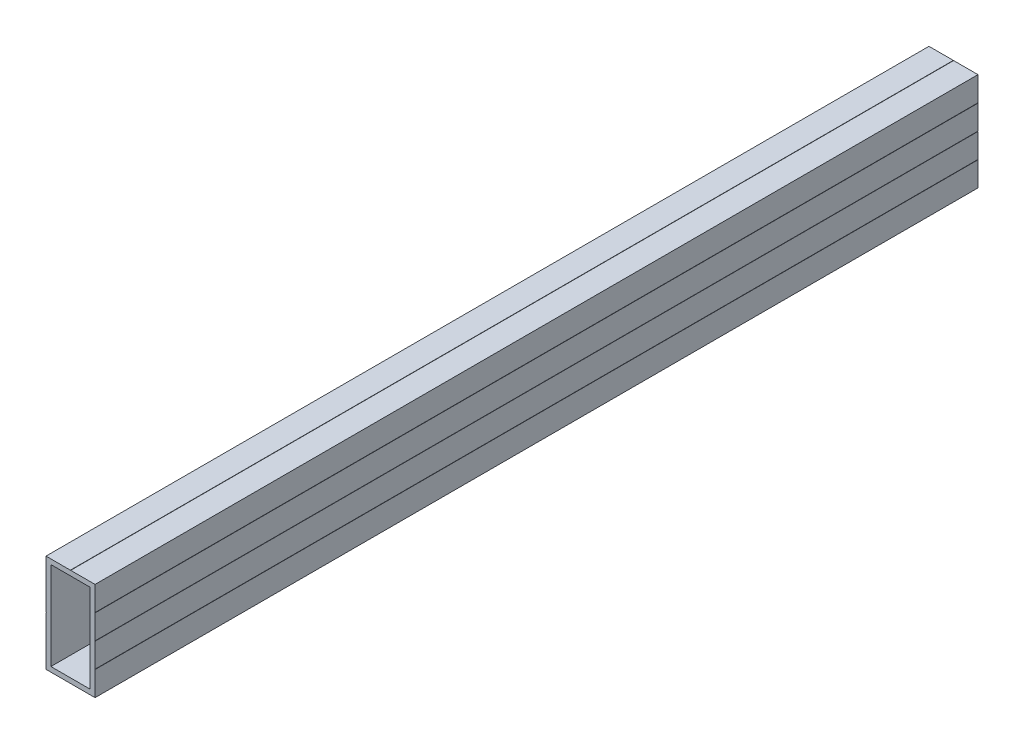
SolidWorks part; units mm, degrees
ref_plane "Front Plane" through (0, 0, 0) normal (0, 0, 1) x (1, 0, 0)
ref_plane "Top Plane" through (0, 0, 0) normal (0, 1, 0) x (1, 0, 0)
ref_plane "Right Plane" through (0, 0, 0) normal (1, 0, 0) x (0, 0, -1)
ref_plane "Plane1" through (12.7, 0, 0) normal (1, 0, 0) x (0, 0, -1)
sketch "Sketch1" plane through (12.7, 0, 0) normal (1, 0, 0) x (0, 0, -1)
  line L0 (-749.3, 25.4) -> (-749.3, -25.4)
  line L1 (-749.3, -25.4) -> (749.3, -25.4)
  line L2 (749.3, -25.4) -> (749.3, 25.4)
  line L3 (749.3, 25.4) -> (-749.3, 25.4)
extrude "Boss-Extrude1" add sketch "Sketch1" against normal blind 25.4
sketch "Sketch2" plane through (0, 0, 749.3) normal (0, 0, 1) x (1, 0, 0)
  line L0 (0.0762, 25.4) -> (-0.0762, 25.4)
  line L1 (-0.0762, 25.4) -> (0.0762, 25.2476)
  line L2 (0.0762, 25.2476) -> (0.0762, 25.4)
extrude "Cut-Extrude1" cut sketch "Sketch2" against normal blind 1498.6
sketch "Sketch3" plane through (0, 0, 749.3) normal (0, 0, 1) x (1, 0, 0)
  line L0 (12.7, 12.6238) -> (12.7, 12.7762)
  line L1 (12.7, 12.7762) -> (12.5476, 12.7762)
  line L2 (12.5476, 12.7762) -> (12.7, 12.6238)
extrude "Cut-Extrude2" cut sketch "Sketch3" against normal through all
sketch "Sketch4" plane through (0, 0, 749.3) normal (0, 0, 1) x (1, 0, 0)
  line L0 (12.7, -0.0762) -> (12.7, 0.0762)
  line L1 (12.7, 0.0762) -> (12.5476, -0.0762)
  line L2 (12.5476, -0.0762) -> (12.7, -0.0762)
extrude "Cut-Extrude3" cut sketch "Sketch4" against normal blind 1498.6
sketch "Sketch5" plane through (0, 0, 749.3) normal (0, 0, 1) x (1, 0, 0)
  line L0 (12.7, -12.7762) -> (12.7, -12.6238)
  line L1 (12.7, -12.6238) -> (12.5476, -12.6238)
  line L2 (12.5476, -12.6238) -> (12.7, -12.7762)
extrude "Cut-Extrude4" cut sketch "Sketch5" against normal blind 1498.6
sketch "Sketch6" plane through (0, 0, 749.3) normal (0, 0, 1) x (1, 0, 0)
  line L0 (0.0762, -25.4) -> (-0.0762, -25.2476)
  line L1 (-0.0762, -25.2476) -> (-0.0762, -25.4)
  line L2 (-0.0762, -25.4) -> (0.0762, -25.4)
extrude "Cut-Extrude5" cut sketch "Sketch6" against normal through all
sketch "Sketch7" plane through (0, 0, 749.3) normal (0, 0, 1) x (1, 0, 0)
  line L0 (-12.7, -12.6238) -> (-12.7, -12.7762)
  line L1 (-12.7, -12.7762) -> (-12.5476, -12.7762)
  line L2 (-12.5476, -12.7762) -> (-12.7, -12.6238)
extrude "Cut-Extrude6" cut sketch "Sketch7" against normal through all
sketch "Sketch8" plane through (0, 0, 749.3) normal (0, 0, 1) x (1, 0, 0)
  line L0 (-12.7, 0.0762) -> (-12.7, -0.0762)
  line L1 (-12.7, -0.0762) -> (-12.5476, 0.0762)
  line L2 (-12.5476, 0.0762) -> (-12.7, 0.0762)
extrude "Cut-Extrude7" cut sketch "Sketch8" against normal blind 1498.6
sketch "Sketch9" plane through (0, 0, 749.3) normal (0, 0, 1) x (1, 0, 0)
  line L0 (-12.7, 12.7762) -> (-12.7, 12.6238)
  line L1 (-12.7, 12.6238) -> (-12.5476, 12.6238)
  line L2 (-12.5476, 12.6238) -> (-12.7, 12.7762)
extrude "Cut-Extrude8" cut sketch "Sketch9" against normal blind 1498.6
sketch "Sketch10" plane through (0, 0, 749.3) normal (0, 0, 1) x (1, 0, 0)
  line L0 (10.16, -22.86) -> (10.16, 22.86)
  line L1 (10.16, 22.86) -> (-10.16, 22.86)
  line L2 (-10.16, 22.86) -> (-10.16, -22.86)
  line L3 (-10.16, -22.86) -> (10.16, -22.86)
extrude "Cut-Extrude9" cut sketch "Sketch10" against normal through all
draft "Draft1" type of draft neutral plane draft angle 45 faces to draft 1 face at (0.0762, 25.3238, 0) neutral plane through (-12.7, 25.4, -749.3) neutral plane normal (0, 1, 0) parameters "D1"=45
draft "Draft2" type of draft neutral plane draft angle 45 faces to draft 1 face at (12.6238, 12.7762, 0) neutral plane through (12.7, 0, 0) neutral plane normal (1, 0, 0) parameters "D1"=45
draft "Draft3" type of draft neutral plane draft angle 45 faces to draft 1 face at (-0.0762, -25.3238, 0) neutral plane through (-12.7, -25.4, 749.3) neutral plane normal (0, -1, 0) parameters "D1"=45
draft "Draft4" type of draft neutral plane draft angle 45 faces to draft 1 face at (-12.6238, -12.7762, 0) neutral plane through (-12.7, 0, 0) neutral plane normal (-1, 0, 0) parameters "D1"=45
draft "Draft5" type of draft neutral plane draft angle 45 faces to draft 2 face at (12.6238, -12.6238, 0) face at (12.6238, 0, 0) neutral plane through (12.7, 0, 0) neutral plane normal (1, 0, 0) parameters "D1"=45
draft "Draft6" type of draft neutral plane draft angle 45 faces to draft 2 face at (-12.6238, 0, 0) face at (-12.6238, 12.6238, 0) neutral plane through (-12.7, 0, 0) neutral plane normal (-1, 0, 0) parameters "D1"=45
sketch "Sketch11" plane through (0, 0, -749.3) normal (0, 0, -1) x (-1, 0, 0)
  line L1 (28.0564, 44.6652) -> (-33.9059, 44.6652)
  line L2 (28.0564, 44.6652) -> (28.0564, -44.0138)
  line L3 (28.0564, -44.0138) -> (-33.9059, -44.0138)
  line L4 (-33.9059, 44.6652) -> (-33.9059, -44.0138)
extrude "Cut-Extrude10" cut sketch "Sketch11" against normal blind 1041.4
